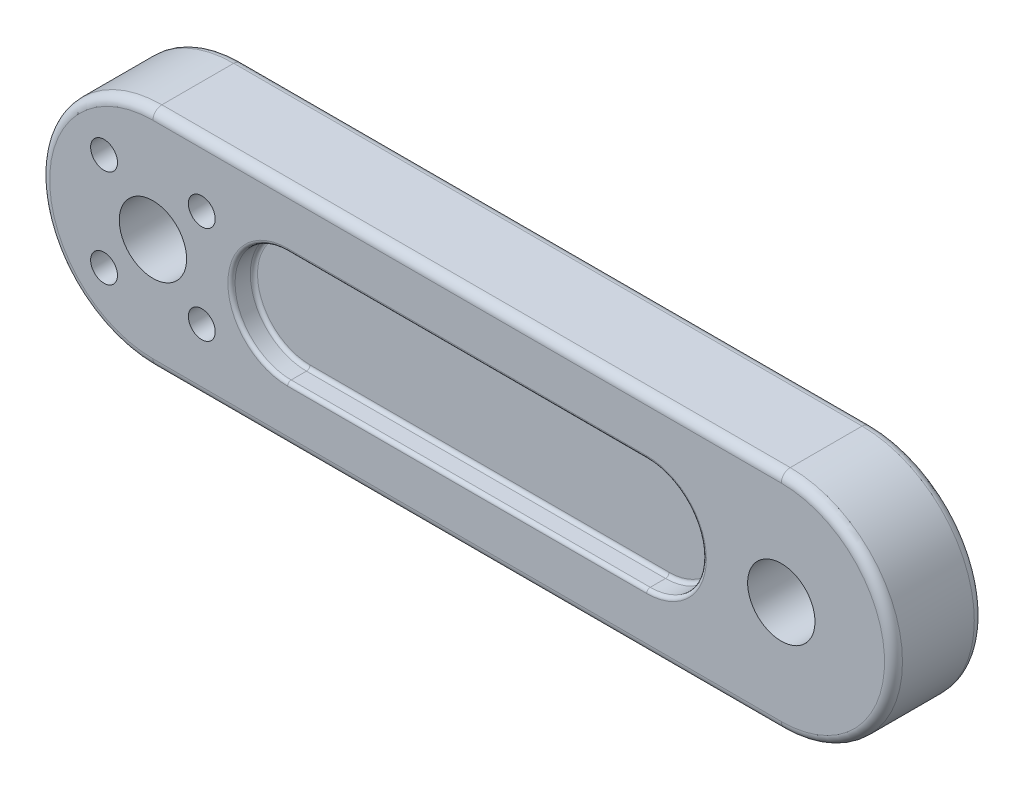
SolidWorks part; units mm, degrees
material "ABS"
ref_plane "Front Plane" through (0, 0, 0) normal (0, 0, 1) x (1, 0, 0)
ref_plane "Top Plane" through (0, 0, 0) normal (0, 1, 0) x (1, 0, 0)
ref_plane "Right Plane" through (0, 0, 0) normal (1, 0, 0) x (0, 0, -1)
sketch "Sketch1" plane through (0, 0, 0) normal (0, 0, 1) x (1, 0, 0)
  line L0 (-60.2655, 7.4906) -> (28.6345, 7.4906) construction
  line L1 (-60.2655, 23.3656) -> (28.6345, 23.3656)
  line L2 (-60.2655, -8.3844) -> (28.6345, -8.3844)
  line L3 (-76.1405, 7.4906) -> (-60.2655, 7.4906) construction
  line L4 (44.5095, 7.4906) -> (28.6345, 7.4906) construction
  arc A0 (-60.2655, 23.3656) -> (-60.2655, -8.3844) centre (-60.2655, 7.4906) ccw
  arc A1 (28.6345, -8.3844) -> (28.6345, 23.3656) centre (28.6345, 7.4906) ccw
  circle A2 centre (-60.2655, 7.4906) radius 4.7625
  circle A3 centre (28.6345, 7.4906) radius 4.7625
  point P2 (-15.8155, 7.4906)
  point P18 (-60.2655, 7.4906)
  dimension "D3" = 9.525
  dimension "D4" = 9.525
  dimension "D1" = 31.75
  dimension "D2" = 88.9
extrude "Boss-Extrude1" add sketch "Sketch1" along normal blind 12.7
sketch "Sketch3" plane through (0, 0, 0) normal (0, 0, -1) x (-1, 0, 0)
  line L0 (51.1336, 7.4906) -> (69.3973, 7.4906) construction
  line L1 (60.2655, 17.6789) -> (60.2655, -2.6976) construction
  line L3 (67.1803, 0.5758) -> (53.3507, 0.5758)
  line L4 (67.1803, 0.5758) -> (67.1803, 14.4054)
  line L5 (67.1803, 14.4054) -> (53.3507, 14.4054)
  line L6 (53.3507, 0.5758) -> (53.3507, 14.4054)
  line L7 (67.1803, 0.5758) -> (53.3507, 14.4054) construction
  line L8 (67.1803, 14.4054) -> (53.3507, 0.5758) construction
  circle A0 centre (60.2655, 7.4906) radius 4.7625 construction
  circle A1 centre (53.3507, 14.4054) radius 1.8986
  circle A2 centre (67.1803, 14.4054) radius 1.8987
  circle A3 centre (67.1803, 0.5758) radius 1.8987
  circle A4 centre (53.3507, 0.5758) radius 1.8986
  point P4 (60.2655, 7.4906)
  point P7 (60.2655, 7.4906)
  dimension "D2" = 3.7973
  dimension "D3" = 3.7973
  dimension "D4" = 3.7973
  dimension "D5" = 3.7973
  dimension "D1" = 19.558
extrude "Cut-Extrude2" cut sketch "Sketch3" against normal blind 12.7 contours L5 A1 L6 | L6 A1 L5 | L6 A4 L3 | L3 A4 L6 | L4 A3 L3 | L3 A3 L4 | L5 A2 L4 | L4 A2 L5
fillet "Fillet1" radius 1.27 8 edges at (-15.8155, -8.3844, 12.7) (44.5095, 7.4906, 12.7) (-76.1405, 7.4906, 12.7) (-15.8155, 23.3656, 12.7) (-76.1405, 7.4906, 0) (-15.8155, -8.3844, 0) (44.5095, 7.4906, 0) (-15.8155, 23.3656, 0)
sketch "Sketch4" plane through (0, 0, 0) normal (0, 0, -1) x (-1, 0, 0)
  line L0 (60.2655, 7.4906) -> (-28.6345, 7.4906) construction
  line L1 (41.2155, 7.4906) -> (-9.5845, 7.4906) construction
  line L2 (41.2155, -0.4469) -> (-9.5845, -0.4469)
  line L3 (41.2155, 15.4281) -> (-9.5845, 15.4281)
  arc A0 (41.2155, -0.4469) -> (41.2155, 15.4281) centre (41.2155, 7.4906) ccw
  arc A1 (-9.5845, 15.4281) -> (-9.5845, -0.4469) centre (-9.5845, 7.4906) ccw
  point P6 (15.8155, 7.4906)
  dimension "D1" = 19.05
  dimension "D2" = 19.05
  dimension "D3" = 15.875
extrude "Cut-Extrude3" cut sketch "Sketch4" against normal blind 3.175
sketch "Sketch5" plane through (0, 0, 12.7) normal (0, 0, 1) x (1, 0, 0)
  line L0 (-60.2655, 7.4906) -> (28.6345, 7.4906) construction
  line L1 (-41.2155, 7.4906) -> (9.5845, 7.4906) construction
  line L2 (-41.2155, 15.4281) -> (9.5845, 15.4281)
  line L3 (-41.2155, -0.4469) -> (9.5845, -0.4469)
  arc A0 (-41.2155, 15.4281) -> (-41.2155, -0.4469) centre (-41.2155, 7.4906) ccw
  arc A1 (9.5845, -0.4469) -> (9.5845, 15.4281) centre (9.5845, 7.4906) ccw
  point P6 (-15.8155, 7.4906)
  dimension "D1" = 19.05
  dimension "D2" = 19.05
  dimension "D3" = 15.875
extrude "Cut-Extrude4" cut sketch "Sketch5" against normal blind 3.175
fillet "Fillet2" radius 0.508 16 edges at (-15.8155, 15.4281, 3.175) (-15.8155, 15.4281, 0) (-49.153, 7.4906, 3.175) (-49.153, 7.4906, 0) (-15.8155, -0.4469, 3.175) (-15.8155, -0.4469, 0) (17.522, 7.4906, 3.175) (17.522, 7.4906, 0) (17.522, 7.4906, 9.525) (17.522, 7.4906, 12.7) (-15.8155, -0.4469, 9.525) (-15.8155, -0.4469, 12.7) (-15.8155, 15.4281, 9.525) (-15.8155, 15.4281, 12.7) (-49.153, 7.4906, 9.525) (-49.153, 7.4906, 12.7)
equation "\"LengthW2W\"=3.5"
equation "\"ShaftD\"= 3 / 8"
equation "\"D3@Sketch1\"=\"ShaftD\""
equation "\"Width\"=1.25"
equation "\"D1@Sketch1\"=\"Width\""
equation "\"OverallThickness\"= 0.5"
equation "\"D1@Boss-Extrude1\"=\"OverallThickness\""
equation "\"HubWholeSep\"=0.54"
equation "\"Hub_6_32_Clearance\"= 0.1495"
equation "\"D2@Sketch3\"=\"Hub_6_32_Clearance\""
equation "\"D3@Sketch3\"=\"Hub_6_32_Clearance\""
equation "\"D4@Sketch3\"=\"Hub_6_32_Clearance\""
equation "\"D5@Sketch3\"=\"Hub_6_32_Clearance\""
equation "\"D1@Sketch4\"=\"ShaftD\"*2"
equation "\"D2@Sketch4\"=\"ShaftD\"*2"
equation "\"D3@Sketch4\"=\"Width\"/2"
equation "\"D1@Cut-Extrude3\"=\"OverallThickness\"/4"
equation "\"D1@Sketch5\"=\"ShaftD\"*2"
equation "\"D2@Sketch5\"=\"ShaftD\"*2"
equation "\"D3@Sketch5\"=\"Width\"/2"
equation "\"D1@Cut-Extrude4\"=\"OverallThickness\"/4"
equation "\"OuterFillet\"= 0.05"
equation "\"InnerFillet\"= 0.02"
equation "\"D1@Fillet2\"=\"InnerFillet\""
equation "\"D1@Fillet1\"=\"OuterFillet\""
equation "\"D4@Sketch1\"=\"ShaftD\""
equation "\"D1@Cut-Extrude2\"=\"OverallThickness\""
